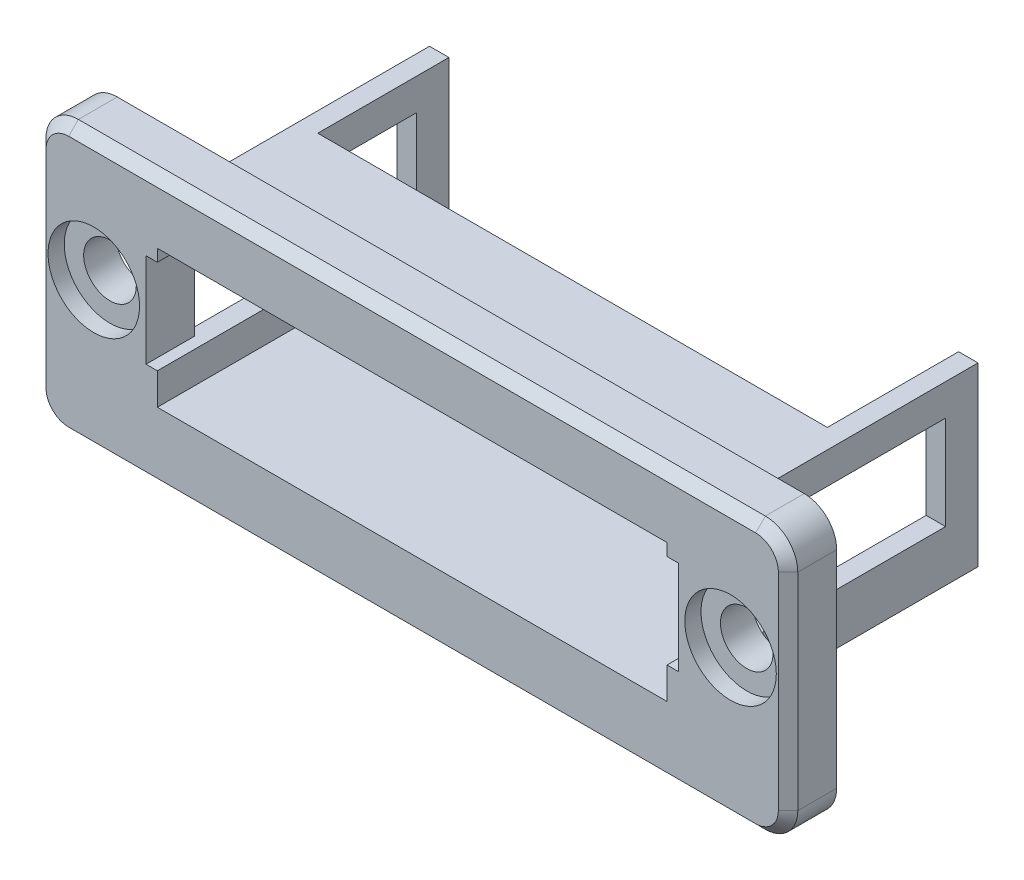
SolidWorks part; units mm, degrees
ref_plane "Front Plane" through (0, 0, 0) normal (0, 0, 1) x (1, 0, 0)
ref_plane "Top Plane" through (0, 0, 0) normal (0, 1, 0) x (1, 0, 0)
ref_plane "Right Plane" through (0, 0, 0) normal (1, 0, 0) x (0, 0, -1)
sketch "SK Flange" plane through (0, 0, 0) normal (0, 0, 1) x (1, 0, 0)
  line L0 (-21.205, -9.25) -> (21.205, -9.25)
  line L1 (23.205, -7.25) -> (23.205, 5.5)
  line L2 (21.205, 7.5) -> (-21.205, 7.5)
  line L3 (-23.205, 5.5) -> (-23.205, -7.25)
  arc A0 (21.205, -9.25) -> (23.205, -7.25) centre (21.205, -7.25) ccw
  arc A1 (23.205, 5.5) -> (21.205, 7.5) centre (21.205, 5.5) ccw
  arc A2 (-21.205, 7.5) -> (-23.205, 5.5) centre (-21.205, 5.5) ccw
  arc A3 (-23.205, -7.25) -> (-21.205, -9.25) centre (-21.205, -7.25) ccw
extrude "Flange" add sketch "SK Flange" along normal blind 3
chamfer "Front bevel" distance 0.6 angle 45 8 edges at (-23.205, -0.875, 3) (-22.6192, 6.9142, 3) (0, 7.5, 3) (22.6192, 6.9142, 3) (23.205, -0.875, 3) (22.6192, -8.6642, 3) (0, -9.25, 3) (-22.6192, -8.6642, 3)
sketch "SK Opening" plane through (0, 0, 0) normal (0, 0, 1) x (1, 0, 0)
  line L0 (-15.73, -4.85) -> (15.73, -4.85)
  line L1 (15.73, -4.85) -> (15.73, -2.9)
  line L2 (15.73, -2.9) -> (16.43, -2.9)
  line L3 (16.43, -2.9) -> (16.43, 2.9)
  line L4 (16.43, 2.9) -> (15.73, 2.9)
  line L5 (15.73, 2.9) -> (15.73, 3.65)
  line L6 (15.73, 3.65) -> (-15.73, 3.65)
  line L7 (-15.73, 3.65) -> (-15.73, 2.9)
  line L8 (-15.73, 2.9) -> (-16.43, 2.9)
  line L9 (-16.43, 2.9) -> (-16.43, -2.9)
  line L10 (-16.43, -2.9) -> (-15.73, -2.9)
  line L11 (-15.73, -2.9) -> (-15.73, -4.85)
  circle A0 centre (-19.655, 0) radius 1.625
  circle A1 centre (19.655, 0) radius 1.625
extrude "Opening + holes" cut sketch "SK Opening" against normal through all and the other way through all
ref_plane "PL front face" through (0, 0, 3) normal (0, 0, 1) x (1, 0, 0)
sketch "SK Counterbore" plane through (0, 0, 3) normal (0, 0, 1) x (1, 0, 0)
  circle A0 centre (-19.655, 0) radius 2.825
  circle A1 centre (19.655, 0) radius 2.825
extrude "Counterbore" cut sketch "SK Counterbore" against normal blind 1
sketch "SK Long walls" plane through (0, 0, 0) normal (0, 0, 1) x (1, 0, 0)
  line L0 (-16.93, 3.65) -> (16.93, 3.65)
  line L1 (16.93, 3.65) -> (16.93, 4.85)
  line L2 (16.93, 4.85) -> (-16.93, 4.85)
  line L3 (-16.93, 4.85) -> (-16.93, 3.65)
  line L4 (-16.93, -6.05) -> (16.93, -6.05)
  line L5 (16.93, -6.05) -> (16.93, -4.85)
  line L6 (16.93, -4.85) -> (-16.93, -4.85)
  line L7 (-16.93, -4.85) -> (-16.93, -6.05)
extrude "Long walls" add sketch "SK Long walls" against normal blind 6.9
sketch "SK Legs" plane through (0, 0, 0) normal (0, 0, 1) x (1, 0, 0)
  line L0 (-15.73, 2.9) -> (-16.93, 2.9)
  line L1 (-16.93, 2.9) -> (-16.93, 4.85)
  line L2 (-16.93, 4.85) -> (-15.73, 4.85)
  line L3 (-15.73, 4.85) -> (-15.73, 2.9)
  line L4 (-15.73, -6.05) -> (-16.93, -6.05)
  line L5 (-16.93, -6.05) -> (-16.93, -2.9)
  line L6 (-16.93, -2.9) -> (-15.73, -2.9)
  line L7 (-15.73, -2.9) -> (-15.73, -6.05)
  line L8 (15.73, 2.9) -> (16.93, 2.9)
  line L9 (16.93, 2.9) -> (16.93, 4.85)
  line L10 (16.93, 4.85) -> (15.73, 4.85)
  line L11 (15.73, 4.85) -> (15.73, 2.9)
  line L12 (15.73, -6.05) -> (16.93, -6.05)
  line L13 (16.93, -6.05) -> (16.93, -2.9)
  line L14 (16.93, -2.9) -> (15.73, -2.9)
  line L15 (15.73, -2.9) -> (15.73, -6.05)
extrude "Legs" add sketch "SK Legs" against normal blind 13
ref_plane "PL leg tips" through (0, 0, -13) normal (0, 0, 1) x (1, 0, 0)
sketch "SK Leg ties" plane through (0, 0, -13) normal (0, 0, 1) x (1, 0, 0)
  line L0 (-15.73, -6.05) -> (-16.93, -6.05)
  line L1 (-16.93, -6.05) -> (-16.93, 4.85)
  line L2 (-16.93, 4.85) -> (-15.73, 4.85)
  line L3 (-15.73, 4.85) -> (-15.73, -6.05)
  line L4 (15.73, -6.05) -> (16.93, -6.05)
  line L5 (16.93, -6.05) -> (16.93, 4.85)
  line L6 (16.93, 4.85) -> (15.73, 4.85)
  line L7 (15.73, 4.85) -> (15.73, -6.05)
extrude "Leg ties" add sketch "SK Leg ties" against normal blind 2
